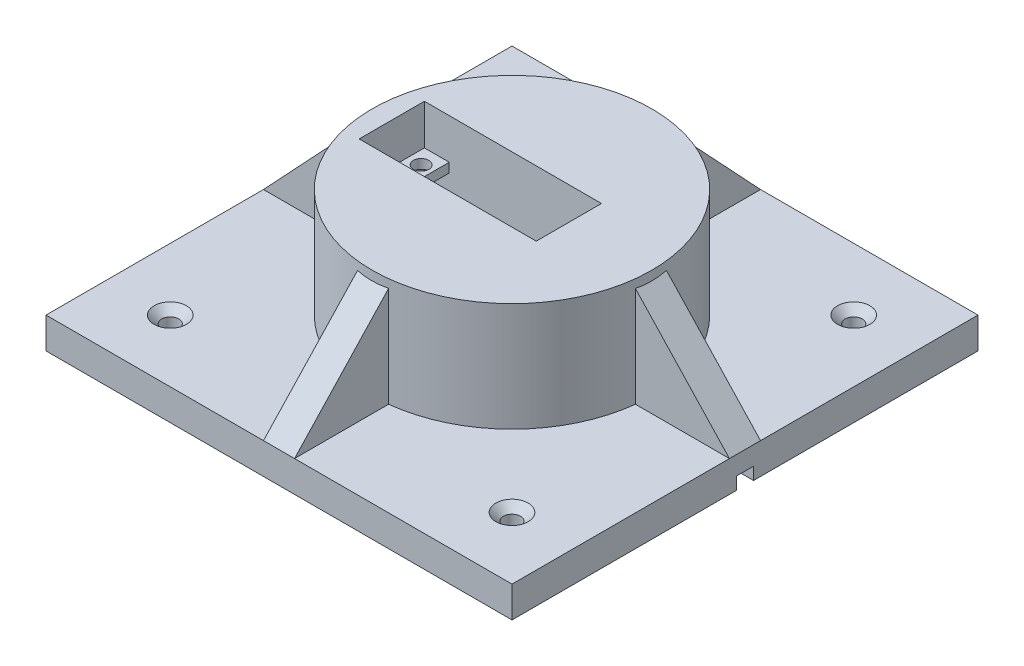
SolidWorks part; units mm, degrees
ref_plane "Front Plane" through (0, 0, 0) normal (0, 0, 1) x (1, 0, 0)
ref_plane "Top Plane" through (0, 0, 0) normal (0, 1, 0) x (1, 0, 0)
ref_plane "Right Plane" through (0, 0, 0) normal (1, 0, 0) x (0, 0, -1)
sketch "Sketch1" plane through (0, 0, 0) normal (0, 1, 0) x (1, 0, 0)
  line L1 (-75, 75) -> (75, 75)
  line L2 (-75, 75) -> (-75, -75)
  line L3 (-75, -75) -> (75, -75)
  line L4 (75, 75) -> (75, -75)
  line L5 (-75, 75) -> (75, -75) construction
  line L6 (-75, -75) -> (75, 75) construction
  point P0 (0, 0)
  dimension "D1" = 150
  dimension "D2" = 150
extrude "Boss-Extrude1" add sketch "Sketch1" along normal blind 10
sketch "Sketch2" plane through (0, 10, 0) normal (0, 1, 0) x (1, 0, 0)
  line L5 (-30.7, 10.5) -> (10.3, 10.5)
  line L6 (-30.7, 10.5) -> (-30.7, -10.5)
  line L7 (-30.7, -10.5) -> (10.3, -10.5)
  line L8 (10.3, 10.5) -> (10.3, -10.5)
  line L9 (-30.7, 10.5) -> (10.3, -10.5) construction
  line L10 (-30.7, -10.5) -> (10.3, 10.5) construction
  circle A0 centre (0, 0) radius 45
  point P0 (0, 0)
  point P1 (-10.2, 0)
  dimension "D3" = 90
  dimension "D1" = 41
  dimension "D2" = 21
  dimension "D4" = 0
  dimension "D5" = 10.2
extrude "Boss-Extrude2" add sketch "Sketch2" along normal blind 35
sketch "Sketch3" plane through (0, 45, 0) normal (0, 1, 0) x (1, 0, 0)
  line L0 (10.3, -10.5) -> (10.3, 10.5) construction
  line L2 (10.3, 10.5) -> (-30.7, 10.5) construction
  line L3 (-38.7, -10.5) -> (18.3, -10.5)
  line L4 (-38.7, -10.5) -> (-38.7, 10.5)
  line L5 (-38.7, 10.5) -> (18.3, 10.5)
  line L6 (18.3, -10.5) -> (18.3, 10.5)
  line L7 (-38.7, -10.5) -> (18.3, 10.5) construction
  line L8 (-38.7, 10.5) -> (18.3, -10.5) construction
  line L11 (-30.7, -10.5) -> (10.3, -10.5) construction
  point P0 (-10.2, -10.5)
  point P3 (-10.2, 0)
  point P29 (10.3, 0)
  dimension "D1" = 57
extrude "Cut-Extrude1" cut sketch "Sketch3" against normal blind 13
sketch "Sketch5" plane through (0, 0, 0) normal (0, -1, 0) x (1, 0, 0)
  line L4 (18.3, 10.5) -> (18.3, -10.5)
  line L5 (18.3, -10.5) -> (-38.7, -10.5)
  line L6 (-38.7, 10.5) -> (18.3, 10.5)
  line L7 (-38.7, -10.5) -> (-38.7, 10.5)
  line L8 (-38.7, 10.5) -> (18.3, -10.5) construction
  point P2 (-10.2, 0)
  dimension "D1" = 57
  dimension "D2" = 21
  dimension "D3" = 10.2
extrude "Cut-Extrude3" cut sketch "Sketch5" against normal offset from surface (29 mm away) 3 up to face at (14.3, 32, 0)
sketch "Sketch6" plane through (0, 0, 0) normal (1, 0, 0) x (0, 0, -1)
  line L0 (45, 42) -> (75, 10)
  line L11 (45, 45) -> (-45, 45) construction
  dimension "D1" = 3
  dimension "D2" = 30
rib "Rib5" sketch "Sketch6" sketch "Sketch6" thickness 10 extrusion direction parallel to sketch draft on no parameters "D1"=10
pattern_circular "CirPattern1" count 4 over 360 about axis through (0, 0, 0) along (0, 1, 0) of "Rib5"
sketch "Sketch9" plane through (0, 10, 0) normal (0, 1, 0) x (1, 0, 0)
  line L0 (55, 55) -> (-55, 55) construction
  line L1 (-55, 55) -> (-55, -55) construction
  line L2 (55, 55) -> (-55, -55) construction
  point P0 (-55, -55)
  point P1 (55, -55)
  point P2 (55, 55)
  point P3 (-55, 55)
  dimension "D1" = 110
hole_wizard "CSK for M5 Countersunk Flat Head Screw1" positions "Sketch10" profile "Sketch11" countersink size "M5" standard "ISO" end condition through all
sketch "Sketch10" plane through (0, 10, 0) normal (0, 1, 0) x (1, 0, 0)
  point P0 (55, -55)
  point P3 (-55, -55)
  point P6 (-55, 55)
  point P9 (55, 55)
sketch "Sketch11" plane through (55, 10, 55) normal (1, 0, 0) x (0, 0, 1)
  line L0 (0, 0) -> (0, 10)
  line L1 (0, 10) -> (2.75, 10)
  line L2 (2.75, 10) -> (2.75, 2.45)
  line L3 (2.75, 2.45) -> (5.2, 0)
  line L5 (5.2, 0) -> (0, 0)
  line L6 (-2.75, 2.45) -> (-5.2, 0) construction
  line L11 (0, -6.35) -> (0, 107.95) construction
  dimension "Thru Hole Dia." = 5.5
  dimension "Thru Hole Depth" = 10
  dimension "Near C'Sink Dia." = 10.4
  dimension "Near C'Sink Angle" = 90
sketch "Sketch12" plane through (0, 32, 0) normal (0, 1, 0) x (1, 0, 0)
  line L1 (-38.7, 10.5) -> (-38.7, -10.5) construction
  line L2 (-30.7, 10.5) -> (-38.7, 10.5) construction
  circle A0 centre (-34.5, 5.25) radius 2.5
  circle A1 centre (-34.5, -4.75) radius 2.5
  circle A2 centre (14.5, 5.25) radius 2.5
  circle A3 centre (14.5, -5) radius 2.5
  dimension "D1" = 4.2
  dimension "D4" = 5
  dimension "D5" = 49
  dimension "D2" = 5.25
  dimension "D3" = 10
extrude "Cut-Extrude4" cut sketch "Sketch12" against normal blind 10
sketch "Sketch13" plane through (-38.7, 0, 0) normal (1, 0, 0) x (0, 0, -1)
  line L0 (-2.75, 0) -> (-2.75, 4)
  line L1 (-10.5, 0) -> (10.5, 0) construction
  line L2 (-2.75, 4) -> (2.75, 4)
  line L3 (2.75, 4) -> (2.75, 0)
  line L4 (0, 0) -> (0, 2.4869) construction
  line L5 (-2.75, 0) -> (2.75, 0)
  dimension "D1" = 4
  dimension "D2" = 5.5
extrude "Cut-Extrude5" cut sketch "Sketch13" against normal through all both and the other way through all
